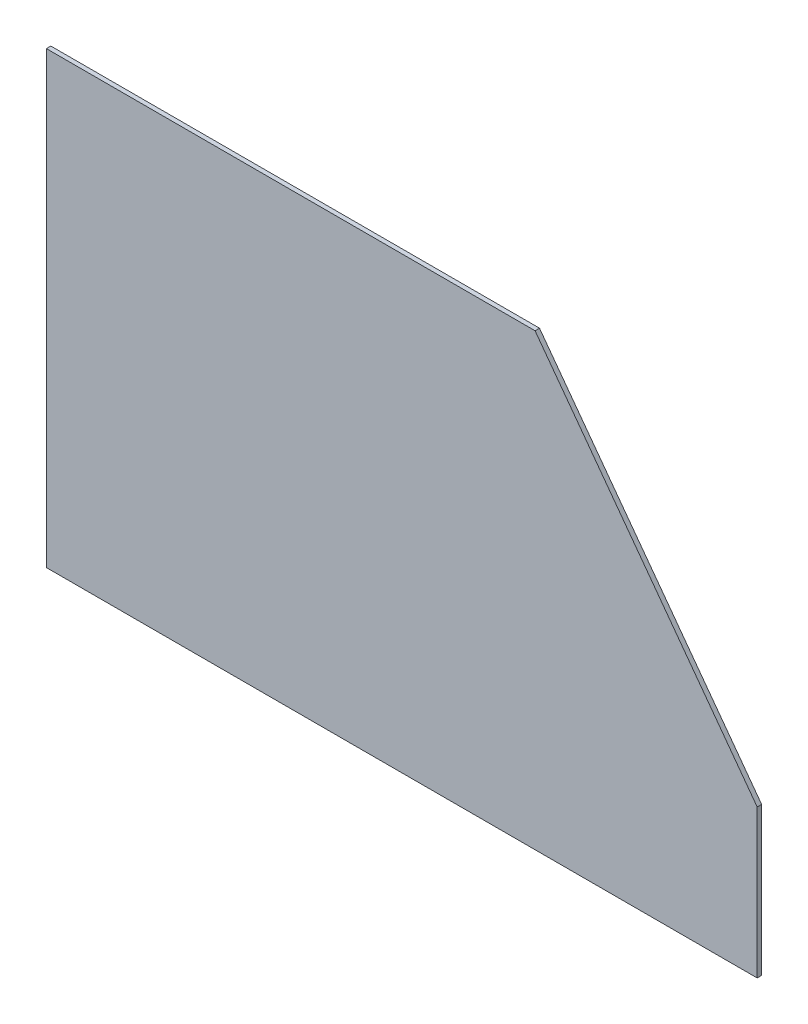
SolidWorks part; units mm, degrees
ref_plane "Front Plane" through (0, 0, 0) normal (0, 0, 1) x (1, 0, 0)
ref_plane "Top Plane" through (0, 0, 0) normal (0, 1, 0) x (1, 0, 0)
ref_plane "Right Plane" through (0, 0, 0) normal (1, 0, 0) x (0, 0, -1)
sketch "Sketch1" plane through (0, 0, 0) normal (0, 0, 1) x (1, 0, 0)
  line L0 (0, 0) -> (480, 0)
  line L1 (480, 0) -> (480, 100)
  line L2 (480, 100) -> (330, 303.5)
  line L3 (330, 303.5) -> (0, 303.5)
  line L4 (0, 303.5) -> (0, 0)
  dimension "D1" = 480
  dimension "D2" = 303.5
  dimension "D3" = 330
  dimension "D4" = 100
extrude "Boss-Extrude1" add sketch "Sketch1" along normal blind 3
